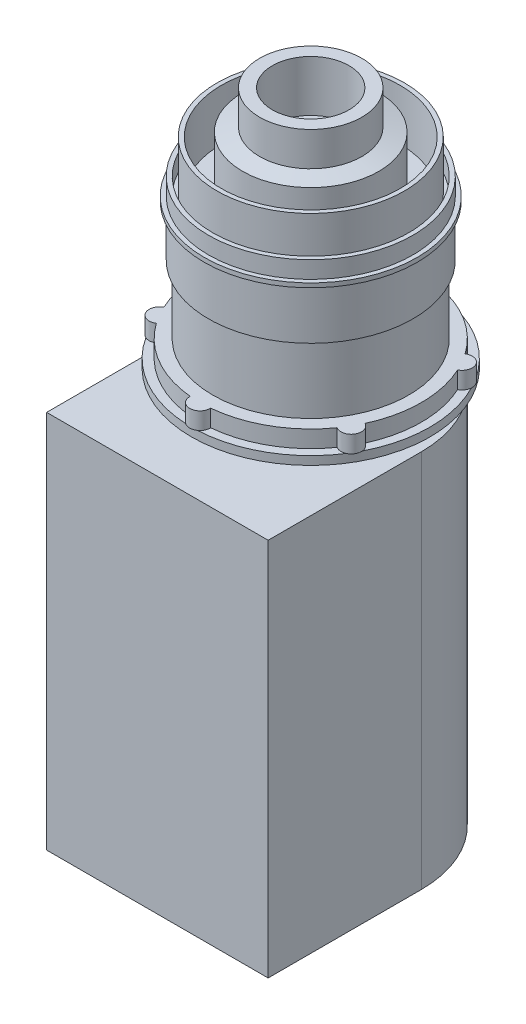
SolidWorks part; units mm, degrees
ref_plane "Front Plane" through (0, 0, 0) normal (0, 0, 1) x (1, 0, 0)
ref_plane "Top Plane" through (0, 0, 0) normal (0, 1, 0) x (1, 0, 0)
ref_plane "Right Plane" through (0, 0, 0) normal (1, 0, 0) x (0, 0, -1)
sketch "Sketch1" plane through (0, 0, 0) normal (0, 1, 0) x (1, 0, 0)
  line L0 (-41.275, 0) -> (41.275, 0)
  line L1 (-41.275, 0) -> (-41.275, 57.15)
  line L2 (41.275, 0) -> (41.275, 57.15)
  line L3 (41.275, 57.15) -> (-41.275, 57.15) construction
  line L4 (0, 85.4181) -> (0, -26.5122) construction
  arc A0 (-41.275, 57.15) -> (41.275, 57.15) centre (0, 57.15) cw
  dimension "D1" = 82.55
  dimension "D2" = 41.275
  dimension "D3" = 57.15
extrude "Boss-Extrude1" add sketch "Sketch1" along normal blind 139.7
shell "Shell1" thickness 1.5875
sketch "Sketch2" plane through (0, 139.7, 0) normal (0, 1, 0) x (1, 0, 0)
  line L6 (41.275, 0) -> (41.275, 57.15) construction
  line L7 (-41.275, 0) -> (41.275, 0) construction
  line L8 (-41.275, 0) -> (-41.275, 57.15) construction
  line L9 (41.275, 0) -> (41.275, 57.15)
  line L10 (-41.275, 0) -> (41.275, 0)
  line L11 (-41.275, 0) -> (-41.275, 57.15)
  arc A2 (41.275, 57.15) -> (-41.275, 57.15) centre (0, 57.15) ccw construction
  arc A3 (41.275, 57.15) -> (-41.275, 57.15) centre (0, 57.15) ccw
extrude "Boss-Extrude2" add sketch "Sketch2" along normal blind 1.5875
sketch "Sketch3" plane through (0, 141.2875, 0) normal (0, 1, 0) x (1, 0, 0)
  circle A0 centre (0, 57.15) radius 31.75
  dimension "D1" = 63.5
extrude "Boss-Extrude3" add sketch "Sketch3" along normal blind 6.35
sketch "Sketch4" plane through (0, 147.6375, 0) normal (0, 1, 0) x (1, 0, 0)
  circle A0 centre (0, 57.15) radius 44.45
  dimension "D1" = 88.9
extrude "Boss-Extrude4" add sketch "Sketch4" along normal blind 3.175
sketch "Sketch5" plane through (0, 150.8125, 0) normal (0, 1, 0) x (1, 0, 0)
  arc A0 (-3.8059, 98.2492) -> (-33.6899, 80.9956) centre (0, 57.15) ccw
  arc A1 (-3.8059, 98.2492) -> (3.8059, 98.2492) centre (0, 98.425) cw
  arc A2 (33.6899, 80.9956) -> (37.4959, 74.4035) centre (35.7452, 77.7875) cw
  arc A3 (37.4959, 39.8965) -> (33.6899, 33.3044) centre (35.7452, 36.5125) cw
  arc A4 (3.8059, 16.0508) -> (-3.8059, 16.0508) centre (0, 15.875) cw
  arc A5 (-33.6899, 33.3044) -> (-37.4959, 39.8965) centre (-35.7452, 36.5125) cw
  arc A6 (-37.4959, 74.4035) -> (-33.6899, 80.9956) centre (-35.7452, 77.7875) cw
  arc A7 (-37.4959, 74.4035) -> (-37.4959, 39.8965) centre (0, 57.15) ccw
  arc A8 (-33.6899, 33.3044) -> (-3.8059, 16.0508) centre (0, 57.15) ccw
  arc A9 (3.8059, 16.0508) -> (33.6899, 33.3044) centre (0, 57.15) ccw
  arc A10 (37.4959, 39.8965) -> (37.4959, 74.4035) centre (0, 57.15) ccw
  arc A11 (33.6899, 80.9956) -> (3.8059, 98.2492) centre (0, 57.15) ccw
  dimension "D1" = 82.55
  dimension "D2" = 3.81
  dimension "D3" = 6
extrude "Boss-Extrude5" add sketch "Sketch5" along normal blind 6.35
sketch "Sketch6" plane through (0, 157.1625, 0) normal (0, 1, 0) x (1, 0, 0)
  circle A0 centre (0, 57.15) radius 36.5125
  dimension "D1" = 73.025
extrude "Boss-Extrude6" add sketch "Sketch6" along normal blind 25.4
sketch "Sketch8" plane through (0, 182.5625, 0) normal (0, 1, 0) x (1, 0, 0)
  circle A0 centre (0, 57.15) radius 38.1
  dimension "D1" = 76.2
extrude "Boss-Extrude7" add sketch "Sketch8" along normal blind 19.05
sketch "Sketch9" plane through (0, 201.6125, 0) normal (0, 1, 0) x (1, 0, 0)
  line L0 (41.275, 57.15) -> (-41.275, 57.15) construction
  circle A0 centre (0, 57.15) radius 39.6875
  dimension "D1" = 79.375
extrude "Boss-Extrude8" add sketch "Sketch9" along normal blind 1.5875
sketch "Sketch10" plane through (0, 203.2, 0) normal (0, 1, 0) x (1, 0, 0)
  circle A0 centre (0, 57.15) radius 38.1
  circle A1 centre (0, 57.15) radius 36.5125
  dimension "D1" = 76.2
  dimension "D2" = 73.025
extrude "Boss-Extrude9" add sketch "Sketch10" along normal blind 6.35
sketch "Sketch12" plane through (0, 203.2, 0) normal (0, 1, 0) x (1, 0, 0)
  circle A0 centre (0, 57.15) radius 34.925
  circle A1 centre (0, 57.15) radius 33.3375
  dimension "D1" = 69.85
  dimension "D2" = 66.675
extrude "Boss-Extrude10" add sketch "Sketch12" along normal blind 19.05
sketch "Sketch14" plane through (0, 0, 0) normal (1, 0, 0) x (0, 0, -1)
  line L0 (57.15, 235.4929) -> (57.15, 105.0033) construction
  line L1 (57.15, 238.125) -> (76.2, 238.125)
  line L2 (76.2, 238.125) -> (76.2, 225.425)
  line L3 (76.2, 225.425) -> (82.55, 223.8375)
  line L4 (82.55, 223.8375) -> (82.55, 203.2)
  line L5 (90.4875, 203.2) -> (23.8125, 203.2) construction
  line L6 (82.55, 203.2) -> (57.15, 203.2)
  line L7 (57.15, 203.2) -> (57.15, 238.125)
  dimension "D1" = 57.15
  dimension "D2" = 19.05
  dimension "D3" = 34.925
  dimension "D4" = 20.6375
  dimension "D5" = 25.4
  dimension "D6" = 12.7
revolve "Revolve1" add sketch "Sketch14" angle 360 about L0
sketch "Sketch15" plane through (0, 238.125, 0) normal (0, 1, 0) x (1, 0, 0)
  circle A0 centre (0, 57.15) radius 14.2875
  dimension "D1" = 28.575
extrude "Cut-Extrude1" cut sketch "Sketch15" against normal blind 19.05
equation "\"3.2.500in\"=3"
